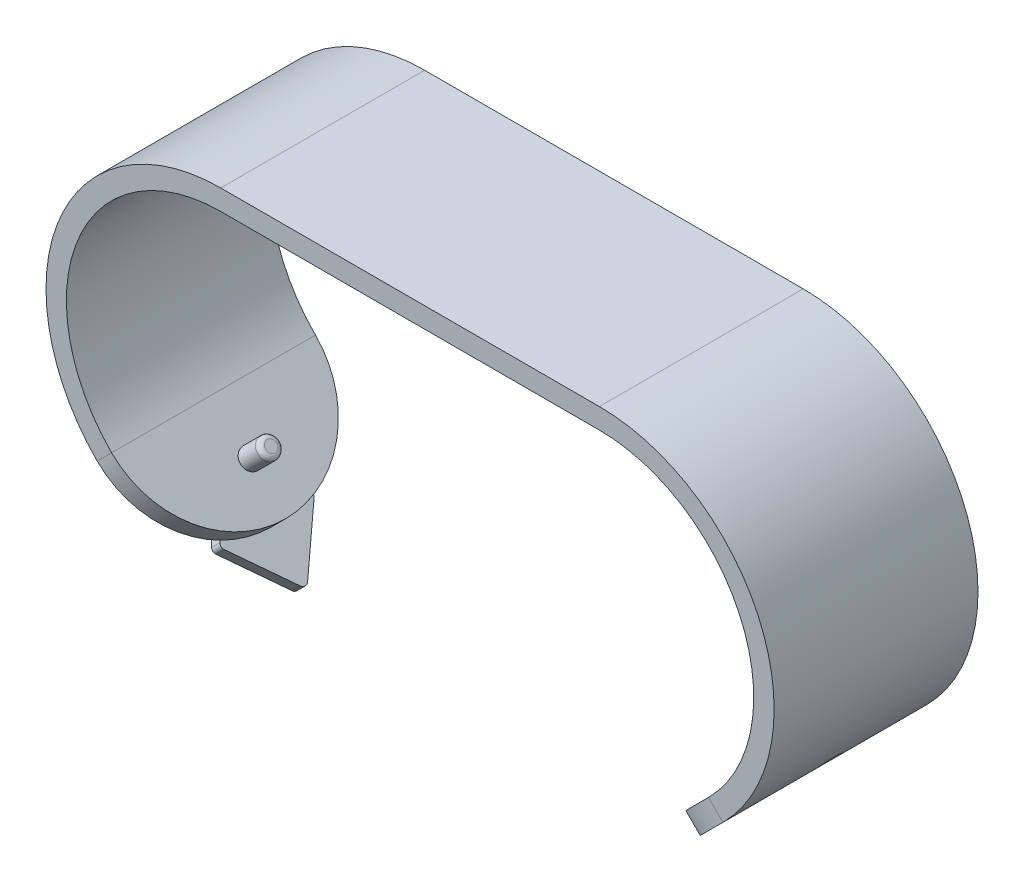
SolidWorks part; units mm, degrees
ref_plane "Front Plane" through (0, 0, 0) normal (0, 0, 1) x (1, 0, 0)
ref_plane "Top Plane" through (0, 0, 0) normal (0, 1, 0) x (1, 0, 0)
ref_plane "Right Plane" through (0, 0, 0) normal (1, 0, 0) x (0, 0, -1)
sketch "Sketch1" plane through (0, 0, 0) normal (0, 0, 1) x (1, 0, 0)
  line L0 (-32.5, 0) -> (32.5, 0)
  line L1 (-32.5, 3.5) -> (32.5, 3.5)
  line L2 (0, 0) -> (0, 29.5125) construction
  line L3 (-53.7132, -47.7132) -> (-51.2383, -45.2383)
  line L4 (-51.2383, -45.2383) -> (-32.5, -26.5) construction
  line L5 (-32.5, -26.5) -> (-32.5, 0)
  line L6 (51.2383, -45.2383) -> (53.7132, -47.7132)
  arc A0 (-32.5, 3.5) -> (-53.7132, -47.7132) centre (-32.5, -26.5) ccw
  arc A1 (-32.5, 0) -> (-51.2383, -45.2383) centre (-32.5, -26.5) ccw
  arc A2 (32.5, 0) -> (51.2383, -45.2383) centre (32.5, -26.5) cw
  arc A3 (32.5, 3.5) -> (53.7132, -47.7132) centre (32.5, -26.5) cw
  point P10 (0, 0)
  dimension "D1" = 3.5
  dimension "D2" = 65
  dimension "D4" = 30
  dimension "D3" = 65
  dimension "D5" = 135
extrude "Boss-Extrude1" add sketch "Sketch1" along normal blind 35 contours A3 L1 A0 L3 A1 L0 A2 L6
ref_plane "Plane1" through (-50.7132, -50.7132, 0) normal (-0.7071, -0.7071, 0) x (0, 0, 1)
sketch "Sketch2" plane through (-50.7132, -50.7132, 0) normal (-0.7071, -0.7071, 0) x (0, 0, 1)
  line L0 (35, 4.2426) -> (0, 4.2426) construction
  line L1 (35, 4.2426) -> (0, 4.2426)
  arc A0 (35, 4.2426) -> (0, 4.2426) centre (17.5, 4.2426) cw
extrude "Boss-Extrude2" add sketch "Sketch2" against normal blind 3.5
mirror "Mirror1" about plane through (0, 0, 0) normal (1, 0, 0) of "Boss-Extrude2"
sketch "Sketch3" plane through (-50.7132, -50.7132, 0) normal (-0.7071, -0.7071, 0) x (0, 0, 1)
  line L0 (17.4026, -2.7244) -> (11.4324, -11.0943)
  line L1 (11.4324, -11.0943) -> (17.4026, -9.0386)
  line L2 (17.4026, -9.0386) -> (17.4026, -2.7244)
  line L3 (11.409, -11.3138) -> (17.4026, -9.2501)
  line L4 (17.4026, -9.2501) -> (17.4026, -14.3677)
  line L5 (17.4026, -14.3677) -> (11.409, -11.3138)
  line L6 (11.5249, -12.7197) -> (17.4026, -15.7145)
  line L7 (17.4026, -15.7145) -> (17.4026, -19.7244)
  line L8 (17.4026, -19.7244) -> (11.5249, -12.7197)
  line L9 (17.5026, -2.7778) -> (17.5026, -17.7182) construction
  line L10 (17.6026, -9.2501) -> (17.6026, -14.3677)
  line L11 (17.6026, -15.7145) -> (17.6026, -19.7244)
  line L12 (17.6026, -19.7244) -> (23.4803, -12.7197)
  line L13 (23.4803, -12.7197) -> (17.6026, -15.7145)
  line L14 (17.6026, -14.3677) -> (23.5961, -11.3138)
  line L15 (23.5961, -11.3138) -> (17.6026, -9.2501)
  line L16 (23.5727, -11.0943) -> (17.6026, -9.0386)
  line L17 (17.6026, -2.7244) -> (23.5727, -11.0943)
  line L18 (17.6026, -9.0386) -> (17.6026, -2.7244)
  line L19 (17.5026, -0.8892) -> (9.3781, -12.2792)
  line L20 (9.3781, -12.2792) -> (17.5026, -21.9616)
  line L21 (17.5026, -21.9616) -> (25.627, -12.2792)
  line L22 (25.627, -12.2792) -> (17.5026, -0.8892)
  point P5 (0, 0)
  point P25 (0, 0)
  point P26 (9.5118, -12.0918)
  dimension "D1" = 109
  dimension "D2" = 35.5
  dimension "D3" = 117
  dimension "D4" = 40
  dimension "D5" = 0.2
  dimension "D6" = 0.1
extrude "Boss-Extrude3" add sketch "Sketch3" along normal blind 2
sketch "Sketch4" plane through (-52.1274, -52.1274, 0) normal (-0.7071, -0.7071, 0) x (0, 0, 1)
  line L3 (17.6026, -15.7145) -> (17.6026, -19.7244)
  line L4 (17.6026, -19.7244) -> (23.4803, -12.7197)
  line L5 (23.4803, -12.7197) -> (17.6026, -15.7145)
  line L6 (17.6026, -15.7145) -> (17.6026, -19.7244)
  line L7 (17.6026, -19.7244) -> (23.4803, -12.7197)
  line L8 (23.4803, -12.7197) -> (17.6026, -15.7145)
  line L9 (17.6026, -9.2501) -> (17.6026, -14.3677)
  line L10 (17.6026, -14.3677) -> (23.5961, -11.3138)
  line L11 (23.5961, -11.3138) -> (17.6026, -9.2501)
  line L12 (17.6026, -9.2501) -> (17.6026, -14.3677)
  line L13 (17.6026, -14.3677) -> (23.5961, -11.3138)
  line L14 (23.5961, -11.3138) -> (17.6026, -9.2501)
  line L15 (17.4026, -15.7145) -> (11.5249, -12.7197)
  line L16 (17.4026, -19.7244) -> (17.4026, -15.7145)
  line L17 (11.5249, -12.7197) -> (17.4026, -19.7244)
  line L18 (17.4026, -15.7145) -> (11.5249, -12.7197)
  line L19 (17.4026, -19.7244) -> (17.4026, -15.7145)
  line L20 (11.5249, -12.7197) -> (17.4026, -19.7244)
  line L21 (17.4026, -9.2501) -> (11.409, -11.3138)
  line L22 (17.4026, -14.3677) -> (17.4026, -9.2501)
  line L23 (11.409, -11.3138) -> (17.4026, -14.3677)
  line L24 (17.4026, -9.2501) -> (11.409, -11.3138)
  line L25 (17.4026, -14.3677) -> (17.4026, -9.2501)
  line L26 (11.409, -11.3138) -> (17.4026, -14.3677)
  line L27 (17.4026, -2.7244) -> (11.4324, -11.0943)
  line L28 (11.4324, -11.0943) -> (17.4026, -9.0386)
  line L29 (17.4026, -9.0386) -> (17.4026, -2.7244)
  line L30 (17.4026, -2.7244) -> (11.4324, -11.0943)
  line L31 (11.4324, -11.0943) -> (17.4026, -9.0386)
  line L32 (17.4026, -9.0386) -> (17.4026, -2.7244)
  line L33 (17.6026, -9.0386) -> (23.5727, -11.0943)
  line L34 (17.5026, -0.8892) -> (9.3781, -12.2792)
  line L35 (9.3781, -12.2792) -> (17.5026, -21.9616)
  line L36 (17.5026, -21.9616) -> (25.627, -12.2792)
  line L37 (25.627, -12.2792) -> (17.5026, -0.8892)
  line L38 (17.5026, -0.8892) -> (9.3781, -12.2792)
  line L39 (9.3781, -12.2792) -> (17.5026, -21.9616)
  line L40 (17.5026, -21.9616) -> (25.627, -12.2792)
  line L41 (25.627, -12.2792) -> (17.5026, -0.8892)
  line L42 (17.6026, -2.7244) -> (17.6026, -9.0386)
  line L43 (23.5727, -11.0943) -> (17.6026, -2.7244)
  line L44 (17.6026, -9.0386) -> (23.5727, -11.0943)
  line L45 (17.6026, -2.7244) -> (17.6026, -9.0386)
  line L46 (23.5727, -11.0943) -> (17.6026, -2.7244)
  dimension "D1" = 0
  dimension "D2" = 0
  dimension "D3" = 0
  dimension "D4" = 0
  dimension "D5" = 0
  dimension "D6" = 0
  dimension "D7" = 0
extrude "Cut-Extrude2" cut sketch "Sketch4" against normal blind 0.5 contours L31 L32 L30 | L44 L46 L45 | L24 L26 L25 | L13 L14 L12 | L18 L20 L19 | L7 L8 L6
fillet "Fillet1" radius 0.8 4 edges at (-50.7916, -52.049, 17.5026) (-42.7376, -60.103, 9.3781) (-42.7376, -60.103, 25.627) (-35.8911, -66.9495, 17.5026)
sketch "Sketch5" plane through (-48.2383, -48.2383, 0) normal (0.7071, 0.7071, 0) x (0, 0, -1)
  line L0 (-17.5, 4.2426) -> (-17.5, -4.7574) construction
  line L1 (-35, 4.2426) -> (0, 4.2426) construction
  circle A0 centre (-17.5, -4.7574) radius 1.75
  dimension "D1" = 3.5
  dimension "D2" = 9
extrude "Boss-Extrude4" add sketch "Sketch5" along normal blind 5
fillet "Fillet2" radius 0.8 1 edges at (-42.5763, -46.8293, 17.5)
sketch "Sketch6" plane through (48.2383, -48.2383, 0) normal (-0.7071, 0.7071, 0) x (0, 0, 1)
  line L0 (35, 4.2426) -> (0, 4.2426) construction
  circle A0 centre (17.5, 4.2426) radius 2.5
  dimension "D1" = 5
extrude "Cut-Extrude4" cut sketch "Sketch6" against normal through all
